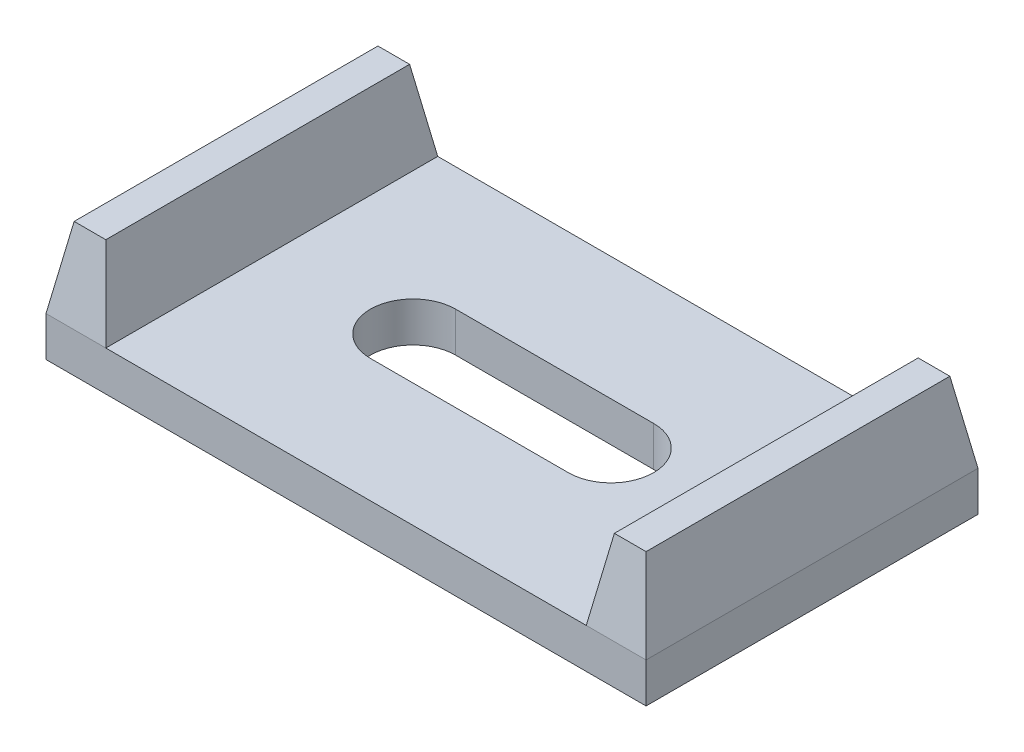
SolidWorks part; units mm, degrees
ref_plane "Front Plane" through (0, 0, 0) normal (0, 0, 1) x (1, 0, 0)
ref_plane "Top Plane" through (0, 0, 0) normal (0, 1, 0) x (1, 0, 0)
ref_plane "Right Plane" through (0, 0, 0) normal (1, 0, 0) x (0, 0, -1)
sketch "Sketch11" plane through (0, 0, 0) normal (0, 1, 0) x (1, 0, 0)
  line L1 (-75.2365, -41.6175) -> (75.2365, -41.6175)
  line L2 (-75.2365, -41.6175) -> (-75.2365, 41.6175)
  line L3 (-75.2365, 41.6175) -> (75.2365, 41.6175)
  line L4 (75.2365, -41.6175) -> (75.2365, 41.6175)
  line L5 (-75.2365, -41.6175) -> (75.2365, 41.6175) construction
  line L6 (-75.2365, 41.6175) -> (75.2365, -41.6175) construction
  point P0 (0, 0)
  dimension "D1" = 150.473
  dimension "D2" = 83.2351
extrude "Boss-Extrude1" add sketch "Sketch11" along normal blind 10
sketch "Sketch13" plane through (0, 10, 0) normal (0, 1, 0) x (1, 0, 0)
  line L0 (-75.2365, -41.6175) -> (75.2365, -41.6175) construction
  line L1 (-75.2365, 41.6175) -> (-60.2365, 41.6175)
  line L2 (-75.2365, 41.6175) -> (-75.2365, -41.6175)
  line L3 (-75.2365, -41.6175) -> (-60.2365, -41.6175)
  line L4 (-60.2365, 41.6175) -> (-60.2365, -41.6175)
  line L6 (75.2365, 41.6175) -> (60.2365, 41.6175)
  line L7 (75.2365, 41.6175) -> (75.2365, -41.6175)
  line L8 (75.2365, -41.6175) -> (60.2365, -41.6175)
  line L9 (60.2365, 41.6175) -> (60.2365, -41.6175)
  point P12 (-60.2365, -41.6175)
  point P13 (0, 0)
  dimension "D1" = 15
  dimension "D2" = 15
extrude "Boss-Extrude2" add sketch "Sketch13" along normal blind 20 draft 10
sketch "Sketch16" plane through (0, 10, 0) normal (0, 1, 0) x (1, 0, 0)
  line L1 (24.821, -10.6959) -> (-24.821, -10.6959)
  line L2 (24.821, -10.6959) -> (24.821, 10.6959)
  line L3 (24.821, 10.6959) -> (-24.821, 10.6959)
  line L4 (-24.821, -10.6959) -> (-24.821, 10.6959)
  line L5 (24.821, -10.6959) -> (-24.821, 10.6959) construction
  line L6 (24.821, 10.6959) -> (-24.821, -10.6959) construction
  circle A0 centre (24.821, 0) radius 10.6959
  circle A1 centre (-24.821, 0) radius 10.6959
  point P0 (0, 0)
extrude "Cut-Extrude17" cut sketch "Sketch16" against normal blind 10 contours L4 A1 | A0
